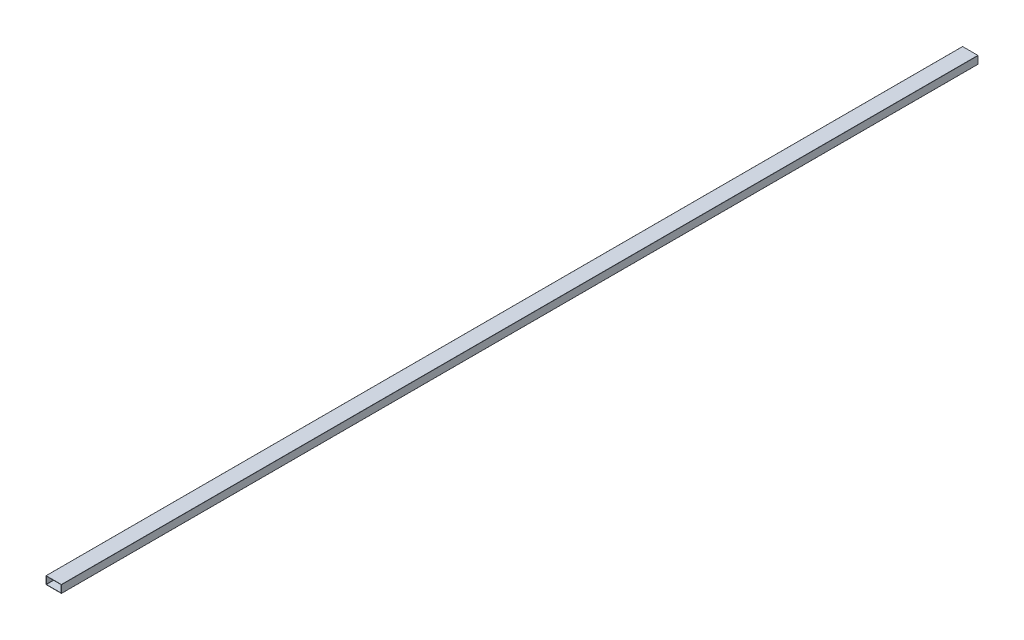
SolidWorks part; units mm, degrees
material "AISI 1035 Acero (SS)"
ref_plane "Alzado" through (0, 0, 0) normal (0, 0, 1) x (1, 0, 0)
ref_plane "Planta" through (0, 0, 0) normal (0, 1, 0) x (1, 0, 0)
ref_plane "Vista lateral" through (0, 0, 0) normal (1, 0, 0) x (0, 0, -1)
sketch "Croquis1" plane through (0, 0, 0) normal (0, 0, 1) x (1, 0, 0)
  line L0 (-48.91, -23.51) -> (-48.91, 23.51)
  line L1 (-50.8, -25.4) -> (50.8, -25.4)
  line L2 (-50.8, -25.4) -> (-50.8, 25.4)
  line L3 (-50.8, 25.4) -> (50.8, 25.4)
  line L4 (50.8, -25.4) -> (50.8, 25.4)
  line L5 (-50.8, -25.4) -> (50.8, 25.4) construction
  line L6 (-50.8, 25.4) -> (50.8, -25.4) construction
  line L7 (-48.91, 23.51) -> (48.91, 23.51)
  line L8 (48.91, -23.51) -> (48.91, 23.51)
  line L9 (-48.91, -23.51) -> (48.91, -23.51)
  point P0 (0, 0)
  dimension "D1" = 50.8
  dimension "D2" = 101.6
  dimension "D3" = 1.89
extrude "Saliente-Extruir1" add sketch "Croquis1" against normal blind 6000
fillet "Redondeo1" radius 1 8 edges at (-48.91, 23.51, -3000) (48.91, 23.51, -3000) (48.91, -23.51, -3000) (-50.8, -25.4, -3000) (-50.8, 25.4, -3000) (-48.91, -23.51, -3000) (50.8, -25.4, -3000) (50.8, 25.4, -3000)
